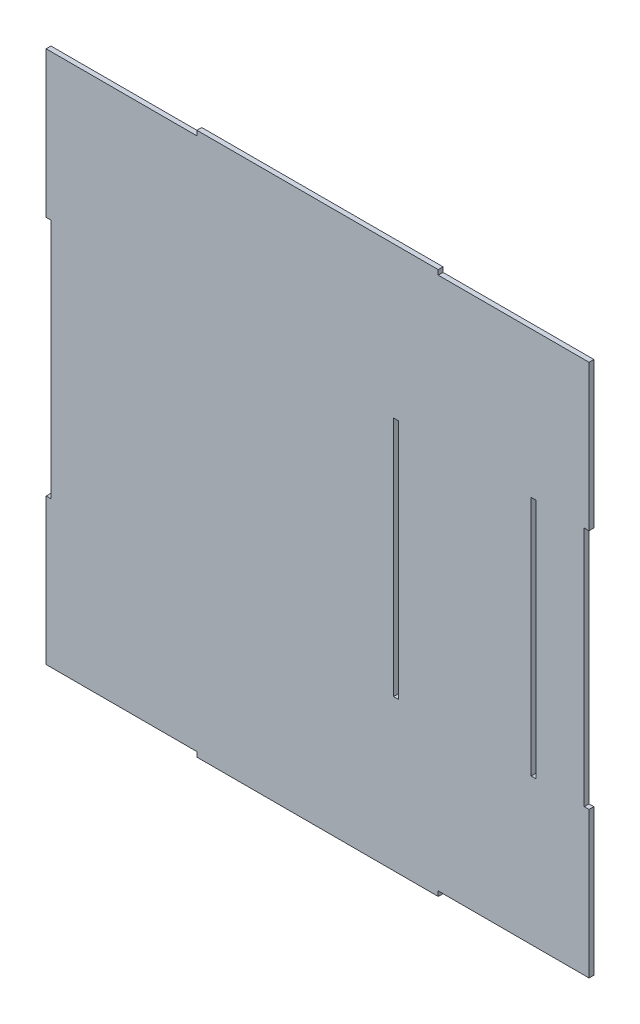
SolidWorks part; units mm, degrees
ref_plane "Front Plane" through (0, 0, 0) normal (0, 0, 1) x (1, 0, 0)
ref_plane "Top Plane" through (0, 0, 0) normal (0, 1, 0) x (1, 0, 0)
ref_plane "Right Plane" through (0, 0, 0) normal (1, 0, 0) x (0, 0, -1)
sketch "Sketch1" plane through (0, 0, 0) normal (0, 0, 1) x (1, 0, 0)
  line L0 (-248.9542, -107.5331) -> (-252.9542, -107.5331)
  line L1 (-252.9542, -107.5331) -> (-252.9542, -228.5331)
  line L2 (-252.9542, -228.5331) -> (-127.9542, -228.5331)
  line L3 (-127.9542, -228.5331) -> (-127.9542, -232.5331)
  line L4 (-127.9542, -232.5331) -> (72.0458, -232.5331)
  line L5 (72.0458, -232.5331) -> (72.0458, -228.5331)
  line L6 (72.0458, -228.5331) -> (197.0458, -228.5331)
  line L7 (197.0458, -228.5331) -> (197.0458, -107.5331)
  line L8 (197.0458, -107.5331) -> (193.0458, -107.5331)
  line L9 (193.0458, -107.5331) -> (193.0458, 92.4669)
  line L10 (193.0458, 92.4669) -> (197.0458, 92.4669)
  line L11 (197.0458, 92.4669) -> (197.0458, 213.4669)
  line L12 (197.0458, 213.4669) -> (72.0458, 213.4669)
  line L13 (72.0458, 213.4669) -> (72.0458, 217.4669)
  line L14 (72.0458, 217.4669) -> (-127.9542, 217.4669)
  line L15 (-127.9542, 217.4669) -> (-127.9542, 213.4669)
  line L16 (-127.9542, 213.4669) -> (-252.9542, 213.4669)
  line L17 (-252.9542, 213.4669) -> (-252.9542, 92.4669)
  line L18 (-252.9542, 92.4669) -> (-248.9542, 92.4669)
  line L19 (-248.9542, 92.4669) -> (-248.9542, -107.5331)
  line L21 (39.0458, 92.4669) -> (35.0458, 92.4669)
  line L22 (39.0458, 92.4669) -> (39.0458, -107.5331)
  line L23 (39.0458, -107.5331) -> (35.0458, -107.5331)
  line L24 (35.0458, 92.4669) -> (35.0458, -107.5331)
  line L25 (149.0458, 92.4669) -> (153.0458, 92.4669)
  line L26 (149.0458, 92.4669) -> (149.0458, -107.5331)
  line L27 (149.0458, -107.5331) -> (153.0458, -107.5331)
  line L28 (153.0458, 92.4669) -> (153.0458, -107.5331)
  dimension "D1" = 4
  dimension "D2" = 110
extrude "Boss-Extrude1" add sketch "Sketch1" along normal blind 4
